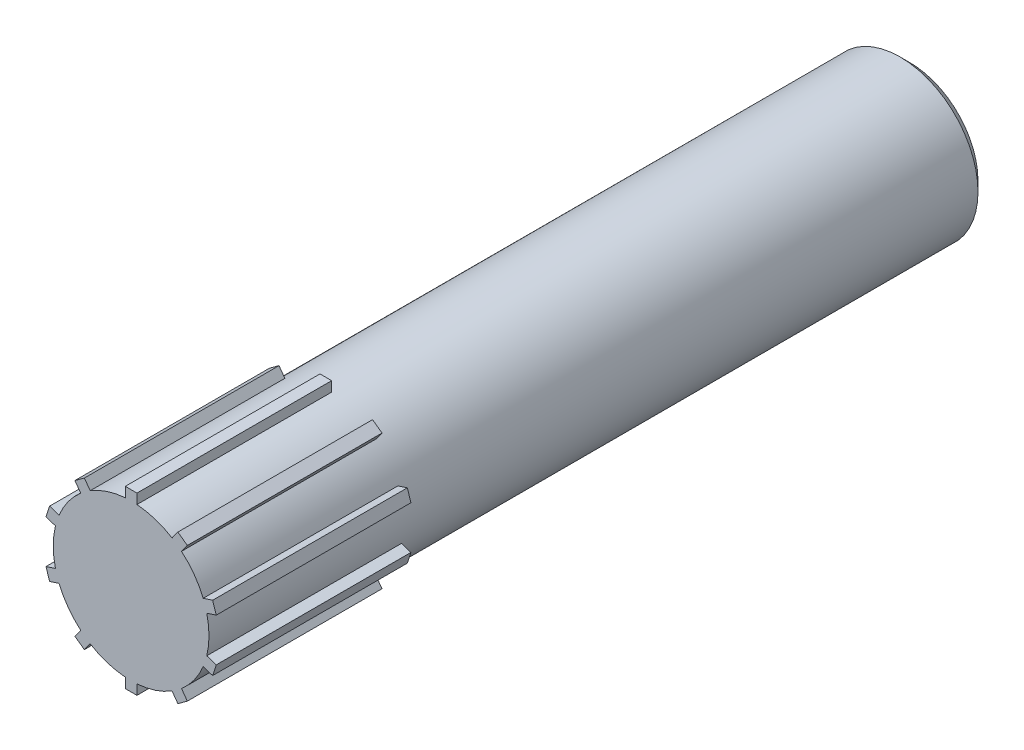
SolidWorks part; units mm, degrees
material "Alloy Steel (SS)"
ref_plane "Front " through (0, 0, 0) normal (0, 0, 1) x (1, 0, 0)
ref_plane "Top " through (0, 0, 0) normal (0, 1, 0) x (1, 0, 0)
ref_plane "Right " through (0, 0, 0) normal (1, 0, 0) x (0, 0, -1)
sketch "Sketch1" plane through (0, 0, 0) normal (0, 0, 1) x (1, 0, 0)
  circle A0 centre (0, 0) radius 4
  dimension "D1" = 8
extrude "Boss-Extrude1" add sketch "Sketch1" along normal blind 40
sketch "Sketch2" plane through (0, 0, 0) normal (0, 1, 0) x (1, 0, 0)
  line L0 (0, 0) -> (0, -40) construction
  line L1 (-4, -40) -> (4, -40) construction
  line L2 (0, -5) -> (0, -9) construction
  line L3 (1.5, -5) -> (1.5, -9)
  line L4 (-1.5, -5) -> (-1.5, -9)
  line L5 (4, 0) -> (-4, 0) construction
  arc A0 (1.5, -5) -> (-1.5, -5) centre (0, -5) ccw
  arc A1 (-1.5, -9) -> (1.5, -9) centre (0, -9) ccw
  point P7 (0, -7)
  dimension "D2" = 1.5
  dimension "D1" = 4
  dimension "D3" = 5
extrude "Cut-Extrude1" cut sketch "Sketch2" against normal through all from offset 2.5 offset against normal yes
sketch "Sketch3" plane through (0, 0, 40) normal (0, 0, 1) x (1, 0, 0)
  line L0 (0, 0) -> (0, 6.6548) construction
  line L2 (0.3, 4.5) -> (-0.3, 4.5)
  line L3 (0.3, 4.5) -> (0.3, 1.9961)
  line L4 (0.3, 1.9961) -> (-0.3, 1.9961)
  line L5 (-0.3, 4.5) -> (-0.3, 1.9961)
  dimension "D1" = 0.6
  dimension "D2" = 4.5
extrude "Boss-Extrude2" add sketch "Sketch3" against normal blind 10
pattern_circular "CirPattern1" count 10 over 360 about axis through (0, 0, 0) along (0, 0, 1) of "Boss-Extrude2"
chamfer "Chamfer1" distance 0.5 angle 45 1 edges at (4, 0, 0)
